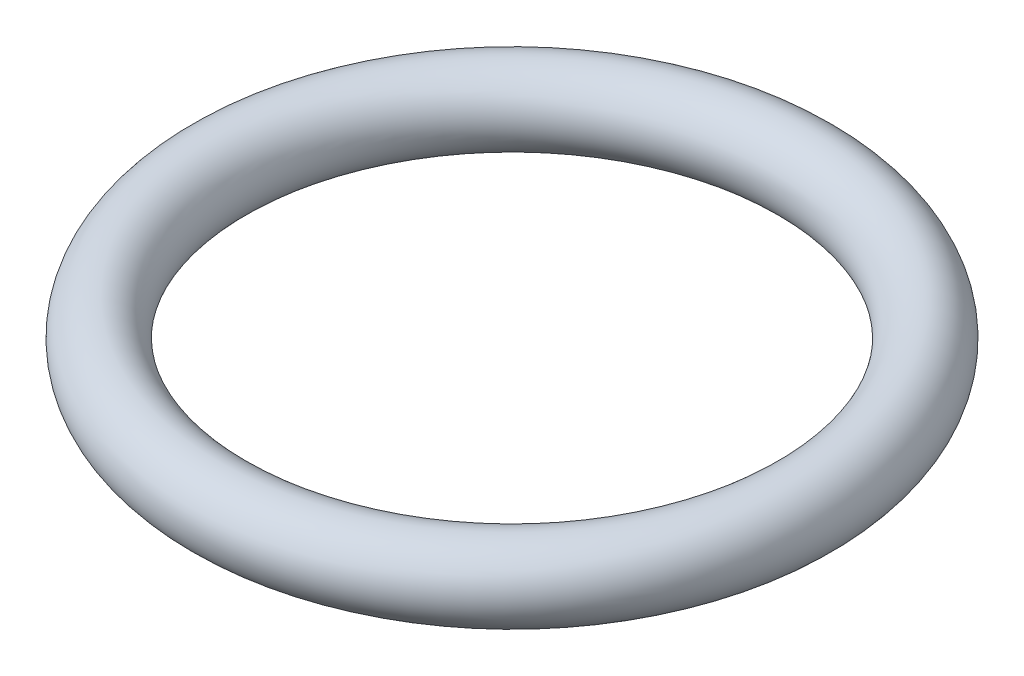
SolidWorks part; units mm, degrees
material "Silicon Rubber"
ref_plane "Front Plane" through (0, 0, 0) normal (0, 0, 1) x (1, 0, 0)
ref_plane "Top Plane" through (0, 0, 0) normal (0, 1, 0) x (1, 0, 0)
ref_plane "Right Plane" through (0, 0, 0) normal (1, 0, 0) x (0, 0, -1)
sketch "Sketch2" plane through (0, 0, 0) normal (0, 0, 1) x (1, 0, 0)
  line L0 (0, 38.7962) -> (0, -25.5762) construction
  line L1 (0, 0) -> (10.8585, 0) construction
  line L2 (10.8585, 0) -> (12.446, 0) construction
  circle A0 centre (12.446, 0) radius 1.5875
  dimension "D2" = 3.175
  dimension "D1" = 10.8585
revolve "Revolve1" add sketch "Sketch2" angle 360 about L0
